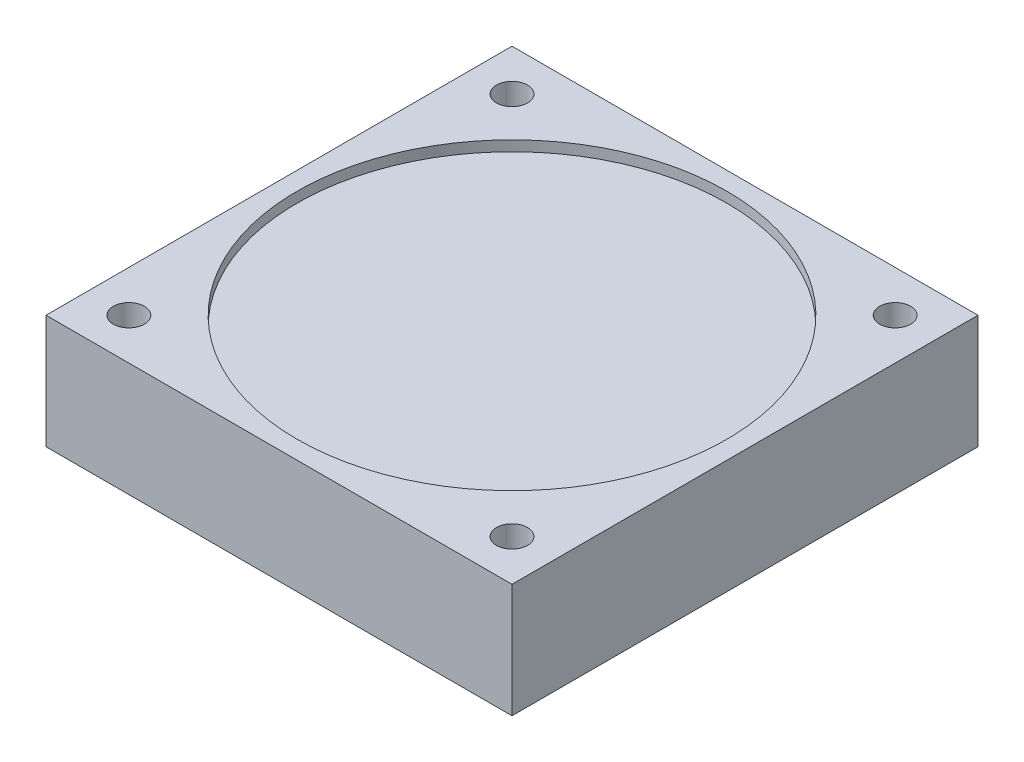
SolidWorks part; units mm, degrees
ref_plane "Front Plane" through (0, 0, 0) normal (0, 0, 1) x (1, 0, 0)
ref_plane "Top Plane" through (0, 0, 0) normal (0, 1, 0) x (1, 0, 0)
ref_plane "Right Plane" through (0, 0, 0) normal (1, 0, 0) x (0, 0, -1)
sketch "Sketch1" plane through (0, 0, 0) normal (0, 1, 0) x (1, 0, 0)
  line L1 (-26.1628, -12.689) -> (18.8372, -12.689)
  line L2 (-26.1628, -12.689) -> (-26.1628, 32.311)
  line L3 (-26.1628, 32.311) -> (18.8372, 32.311)
  line L4 (18.8372, -12.689) -> (18.8372, 32.311)
  circle A0 centre (-22.1628, 28.311) radius 1.5
  circle A1 centre (14.8372, 28.311) radius 1.5
  circle A2 centre (-22.1628, -8.689) radius 1.5
  circle A3 centre (14.8372, -8.689) radius 1.5
  dimension "D9" = 3
  dimension "D10" = 3
  dimension "D11" = 3
  dimension "D12" = 3
  dimension "D1" = 45
  dimension "D2" = 45
  dimension "D3" = 37
  dimension "D4" = 37
  dimension "D5" = 37
  dimension "D6" = 37
  dimension "D7" = 4
  dimension "D8" = 4
extrude "Boss-Extrude1" add sketch "Sketch1" along normal blind 11
sketch "Sketch2" plane through (0, 11, 0) normal (0, 1, 0) x (1, 0, 0)
  line L0 (18.8372, 32.311) -> (-26.1628, 32.311) construction
  line L1 (-26.1628, 32.311) -> (-26.1628, -12.689) construction
  circle A0 centre (-3.6628, 9.811) radius 20.75
  point P4 (-3.6628, 32.311)
  point P7 (-26.1628, 9.811)
  dimension "D1" = 41.5
extrude "Cut-Extrude1" cut sketch "Sketch2" against normal blind 1
